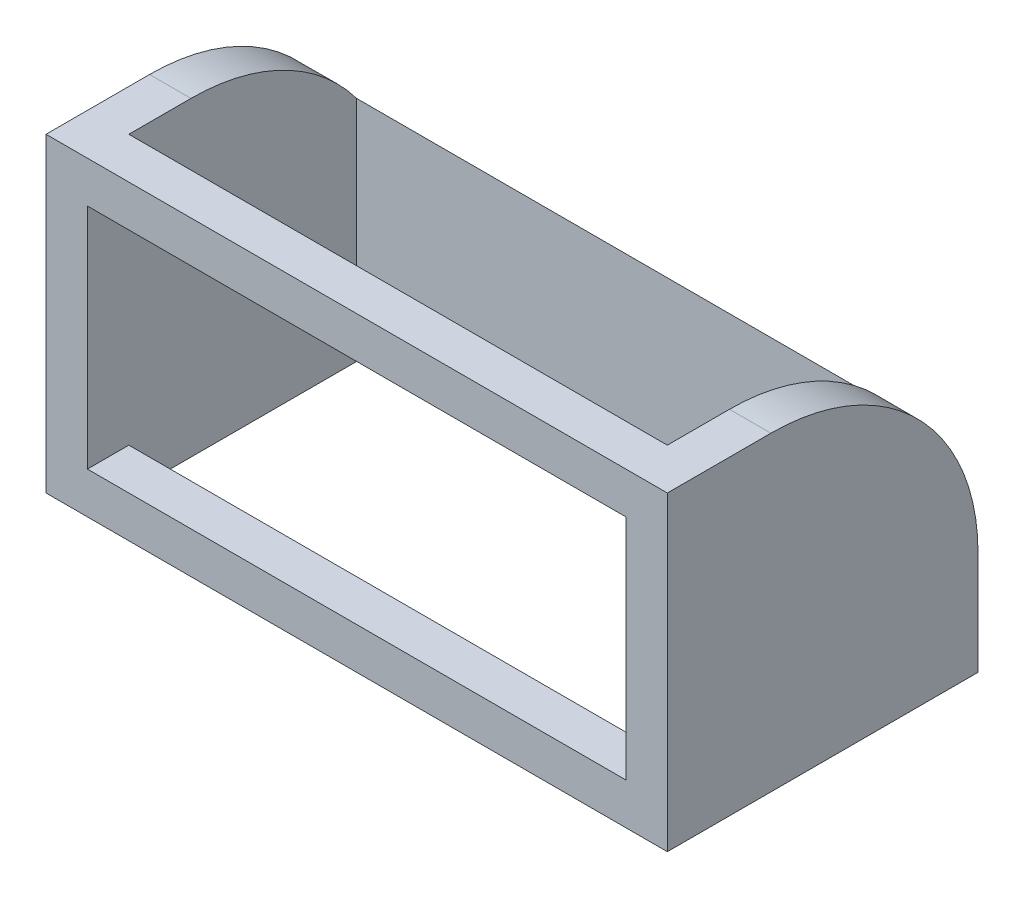
SolidWorks part; units mm, degrees
ref_plane "Front Plane" through (0, 0, 0) normal (0, 0, 1) x (1, 0, 0)
ref_plane "Top Plane" through (0, 0, 0) normal (0, 1, 0) x (1, 0, 0)
ref_plane "Right Plane" through (0, 0, 0) normal (1, 0, 0) x (0, 0, -1)
sketch "Sketch12" plane through (0, 0, 0) normal (0, 1, 0) x (1, 0, 0)
  line L1 (-15, -7.5) -> (15, -7.5)
  line L2 (-15, -7.5) -> (-15, 7.5)
  line L3 (-15, 7.5) -> (15, 7.5)
  line L4 (15, -7.5) -> (15, 7.5)
  line L5 (-15, -7.5) -> (15, 7.5) construction
  line L6 (-15, 7.5) -> (15, -7.5) construction
  point P0 (0, 0)
  dimension "D1" = 15
  dimension "D2" = 30
extrude "Boss-Extrude4" add sketch "Sketch12" along normal blind 15
fillet "Fillet1" radius 10 1 edges at (0, 15, -7.5)
sketch "Sketch13" plane through (0, 0, 0) normal (0, -1, 0) x (1, 0, 0)
  line L1 (13, -5.5) -> (-13, -5.5)
  line L2 (13, -5.5) -> (13, 5.5)
  line L3 (13, 5.5) -> (-13, 5.5)
  line L4 (-13, -5.5) -> (-13, 5.5)
  line L8 (-15, -7.5) -> (-15, 7.5) construction
  line L9 (15, -7.5) -> (-15, -7.5) construction
  line L11 (15, 7.5) -> (15, -7.5) construction
  dimension "D1" = 2
  dimension "D2" = 2
  dimension "D3" = 11
  dimension "D4" = 2
extrude "Cut-Extrude8" cut sketch "Sketch13" against normal through all both and the other way through all
sketch "Sketch14" plane through (0, 0, 7.5) normal (0, 0, 1) x (1, 0, 0)
  line L0 (-15, 15) -> (15, 15) construction
  line L1 (-13, 2) -> (13, 2)
  line L2 (-13, 2) -> (-13, 13)
  line L3 (-13, 13) -> (13, 13)
  line L4 (13, 2) -> (13, 13)
  line L5 (-15, 15) -> (-15, 0) construction
  line L6 (15, 15) -> (15, 0) construction
  line L7 (-15, 0) -> (15, 0) construction
  dimension "D1" = 2
  dimension "D2" = 2
  dimension "D3" = 2
  dimension "D4" = 2
extrude "Cut-Extrude9" cut sketch "Sketch14" against normal blind 10
